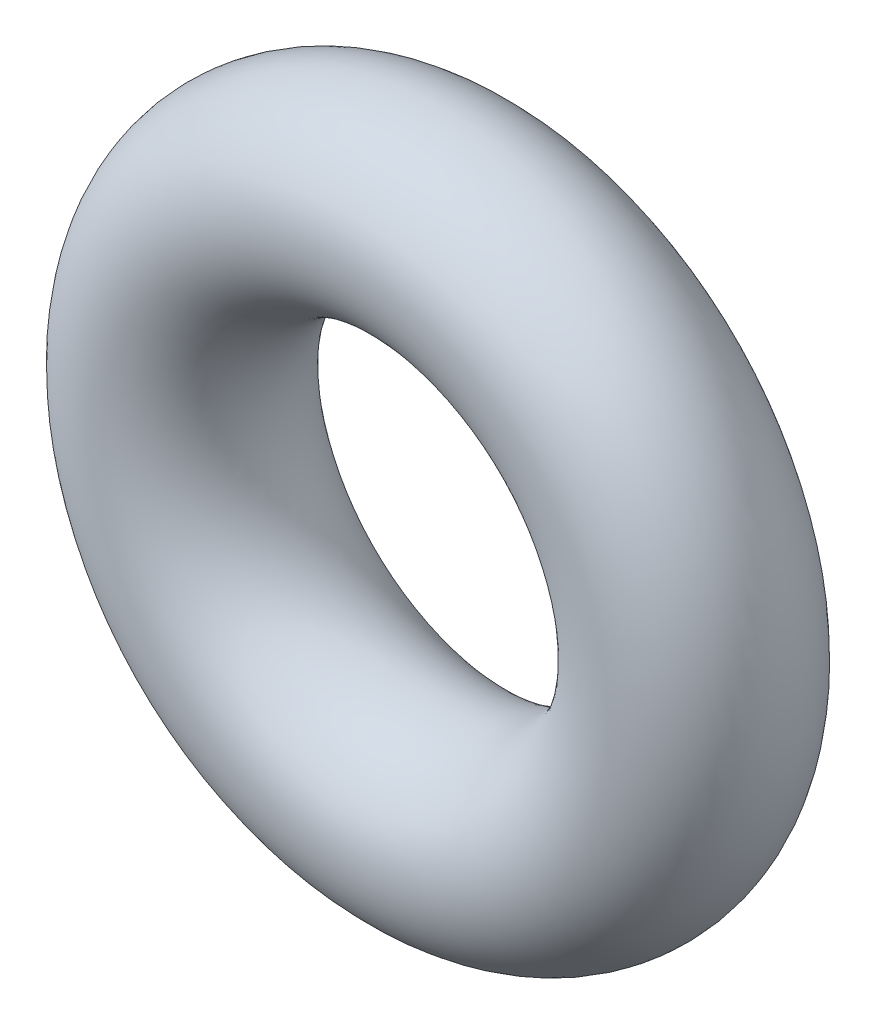
SolidWorks part; units mm, degrees
ref_plane "Front" through (0, 0, 0) normal (0, 0, 1) x (1, 0, 0)
ref_plane "Top" through (0, 0, 0) normal (0, 1, 0) x (1, 0, 0)
ref_plane "Right" through (0, 0, 0) normal (1, 0, 0) x (0, 0, -1)
sketch "Sketch1" plane through (0, 0, 0) normal (1, 0, 0) x (0, -1, 0)
  line L0 (0, -0.75) -> (0, 0.75) construction
  line L2 (-2.475, 0) -> (2.475, 0) construction
  line L3 (-1.25, 0) -> (1.25, 0) construction
  circle A0 centre (2, 0) radius 0.75
  point P9 (1.25, 0)
  point P10 (2.75, 0)
  point P13 (2, 0.75)
  point P14 (2, -0.75)
  dimension "Width" = 1.5
  dimension "ID" = 2.5
revolve "Revolve1" add sketch "Sketch1" angle 360 about L0
